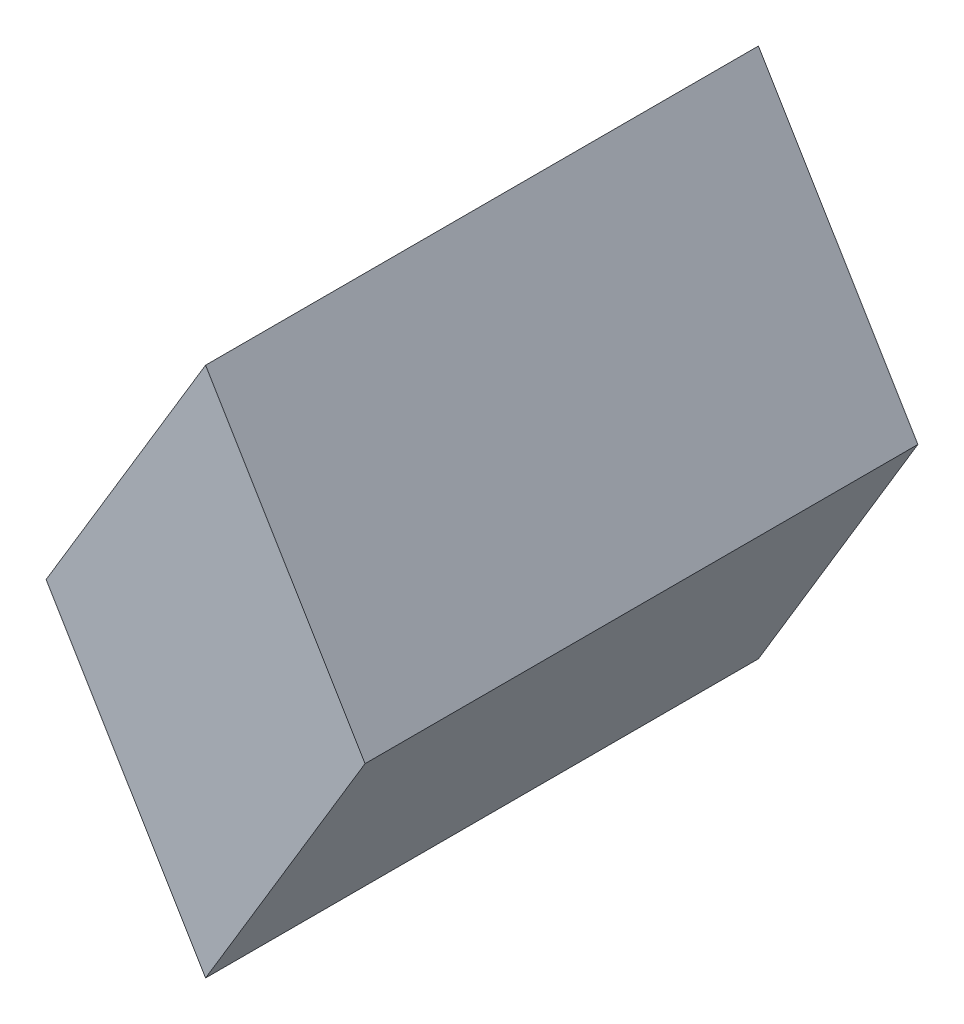
SolidWorks part; units mm, degrees
ref_plane "Alzado" through (0, 0, 0) normal (0, 0, 1) x (1, 0, 0)
ref_plane "Planta" through (0, 0, 0) normal (0, 1, 0) x (1, 0, 0)
ref_plane "Vista lateral" through (0, 0, 0) normal (1, 0, 0) x (0, 0, -1)
sketch "Croquis1" plane through (0, 0, 0) normal (0, 0, 1) x (1, 0, 0)
  line L1 (0, 24.535) -> (14.4222, 0.535)
  line L2 (14.4222, 0.535) -> (0, -23.465)
  line L3 (0, -23.465) -> (-14.4222, 0.535)
  line L4 (-14.4222, 0.535) -> (0, 24.535)
  dimension "D1" = 48
  dimension "D2" = 28
  dimension "D3" = 28
  dimension "D4" = 28
  dimension "D5" = 28
extrude "Saliente-Extruir1" add sketch "Croquis1" along normal blind 50
sketch "Croquis2" plane through (0, 0, 0) normal (0, 0, -1) x (-1, 0, 0)
  circle A0 centre (0, 0) radius 5
  dimension "D1" = 10
extrude "Cortar-Extruir1" cut sketch "Croquis2" against normal blind 10
